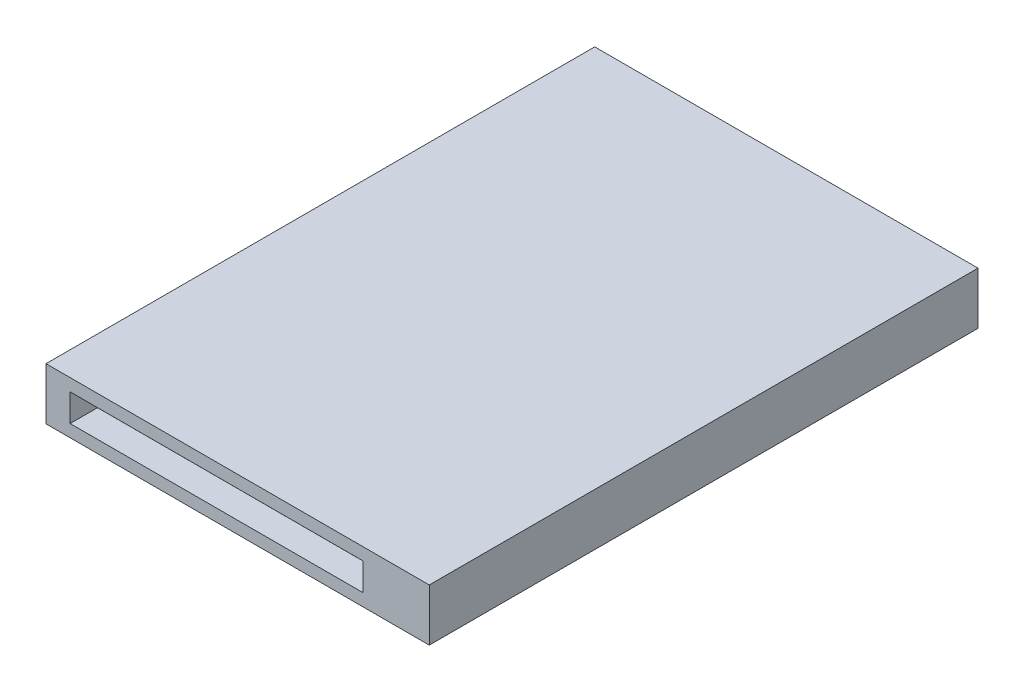
SolidWorks part; units mm, degrees
ref_plane "Přední rovina" through (0, 0, 0) normal (0, 0, 1) x (1, 0, 0)
ref_plane "Horní rovina" through (0, 0, 0) normal (0, 1, 0) x (1, 0, 0)
ref_plane "Pravá rovina" through (0, 0, 0) normal (1, 0, 0) x (0, 0, -1)
sketch "Skica1" plane through (0, 0, 0) normal (0, 1, 0) x (1, 0, 0)
  line L0 (-34.925, -50) -> (34.925, 50) construction
  line L1 (-34.925, 50) -> (34.925, 50)
  line L2 (-34.925, 50) -> (-34.925, -50)
  line L3 (-34.925, -50) -> (34.925, -50)
  line L4 (34.925, 50) -> (34.925, -50)
  dimension "D1" = 100
  dimension "D2" = 69.85
extrude "Přidat vysunutím1" add sketch "Skica1" along normal blind 9.5
sketch "Skica2" plane through (0, 0, 50) normal (0, 0, 1) x (1, 0, 0)
  line L1 (-30.5315, 7.2536) -> (22.8376, 7.2536)
  line L2 (-30.5315, 7.2536) -> (-30.5315, 2.2464)
  line L3 (-30.5315, 2.2464) -> (22.8376, 2.2464)
  line L4 (22.8376, 7.2536) -> (22.8376, 2.2464)
extrude "Odebrat vysunutím1" cut sketch "Skica2" against normal blind 5
